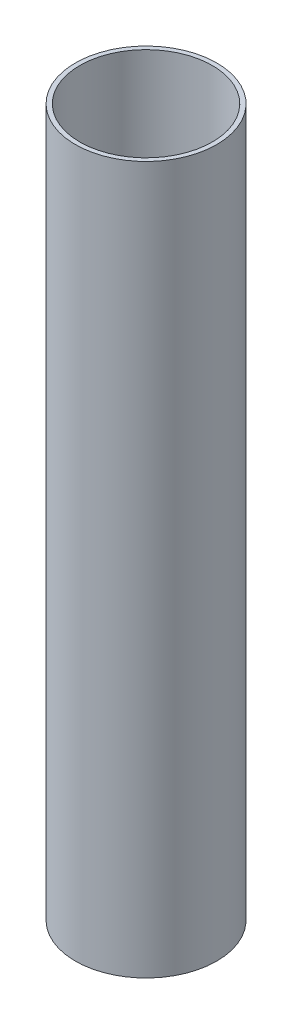
SolidWorks part; units mm, degrees
ref_plane "Front Plane" through (0, 0, 0) normal (0, 0, 1) x (1, 0, 0)
ref_plane "Top Plane" through (0, 0, 0) normal (0, 1, 0) x (1, 0, 0)
ref_plane "Right Plane" through (0, 0, 0) normal (1, 0, 0) x (0, 0, -1)
sketch "Sketch1" plane through (0, 0, 0) normal (0, 1, 0) x (1, 0, 0)
  circle A0 centre (0, 0) radius 19.05
  dimension "D1" = 38.1
extrude "Extrude-Thin1" add sketch "Sketch1" along normal blind 203.2 thin
